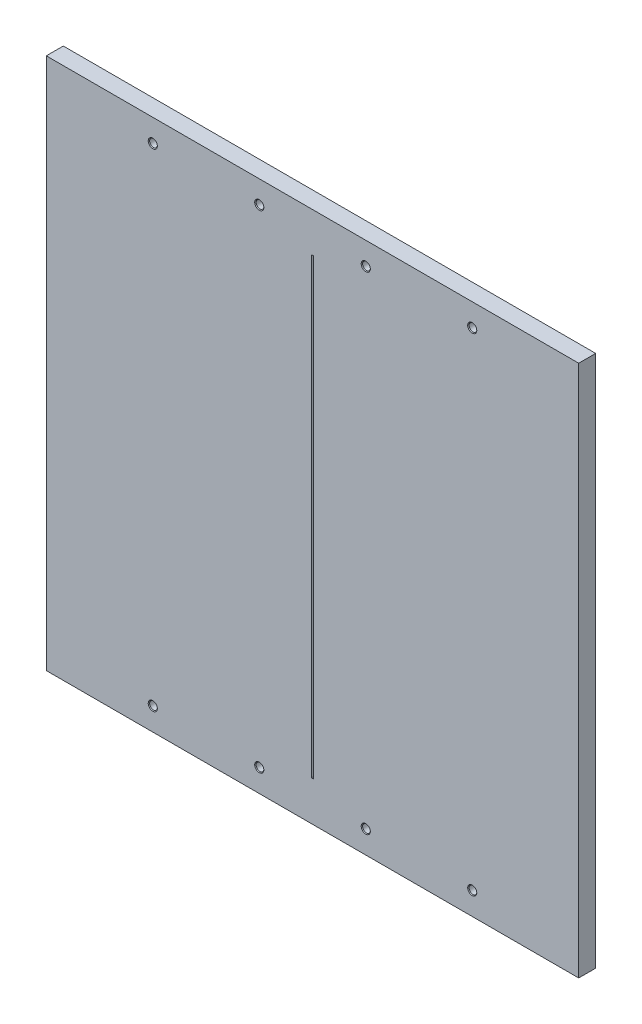
SolidWorks part; units mm, degrees
material "3.0205 (EN-AW 1200)"
ref_plane "Piano frontale" through (0, 0, 0) normal (0, 0, 1) x (1, 0, 0)
ref_plane "Piano superiore" through (0, 0, 0) normal (0, 1, 0) x (1, 0, 0)
ref_plane "Piano destro" through (0, 0, 0) normal (1, 0, 0) x (0, 0, -1)
sketch "Schizzo1" plane through (0, 0, 0) normal (0, 0, 1) x (1, 0, 0)
  line L1 (-235, -235) -> (235, -235)
  line L2 (-235, -235) -> (-235, 235)
  line L3 (-235, 235) -> (235, 235)
  line L4 (235, -235) -> (235, 235)
  line L5 (-235, -235) -> (235, 235) construction
  line L6 (-235, 235) -> (235, -235) construction
  point P0 (0, 0)
  dimension "D1" = 470
  dimension "D2" = 470
extrude "Estrusione-Estrusione1" add sketch "Schizzo1" along normal blind 15
hole_wizard "Foro filettato M8-1" positions "Schizzo8" profile "Schizzo10" tap size "M8" standard "ISO"
sketch "Schizzo8" plane through (0, 0, 15) normal (0, 0, 1) x (1, 0, 0)
  line L0 (-235, 215) -> (235, 215) construction
  line L1 (-235, 235) -> (-235, -235) construction
  line L2 (235, -235) -> (235, 235) construction
  line L4 (235, 235) -> (-235, 235) construction
  line L6 (-235, -215) -> (235, -215) construction
  line L8 (-235, -235) -> (235, -235) construction
  line L9 (-141, 215) -> (-141, -215) construction
  line L11 (-47, 215) -> (-47, -215) construction
  line L13 (47, 215) -> (47, -215) construction
  line L15 (141, 215) -> (141, -215) construction
  point P0 (-141, 215)
  point P2 (-47, 215)
  point P4 (47, 215)
  point P6 (141, 215)
  point P8 (-141, -215)
  point P10 (-47, -215)
  point P14 (141, -215)
  point P16 (47, -215)
  dimension "D1" = 20
  dimension "D2" = 20
  dimension "D3" = 94
  dimension "D4" = 94
  dimension "D5" = 94
  dimension "D6" = 94
sketch "Schizzo10" plane through (-141, 215, 15) normal (1, 0, 0) x (0, -1, 0)
  line L0 (0, 0) -> (0, 24.2929)
  line L1 (0, 24.2929) -> (3.4, 22.25)
  line L2 (3.4, 22.25) -> (3.4, 0.625)
  line L3 (3.4, 0.625) -> (4.025, 0)
  line L5 (4.025, 0) -> (0, 0)
  line L6 (-3.4, 0.625) -> (-4.025, 0) construction
  line L10 (0, 24.2929) -> (-3.4, 22.25) construction
  line L11 (0, -6.35) -> (0, 107.95) construction
  dimension "Tap Drill Dia." = 6.8
  dimension "Tap Drill Depth" = 22.25
  dimension "Near C'Sink Dia." = 8.05
  dimension "Near C'Sink Angle" = 90
  dimension "Drill Angle" = 118
cosmetic thread "Filettatura del foro1" parameters "D1"=16, "D2"=8
cosmetic thread "Filettatura del foro2" parameters "D1"=16, "D2"=8
cosmetic thread "Filettatura del foro3" parameters "D1"=16, "D2"=8
cosmetic thread "Filettatura del foro4" parameters "D1"=16, "D2"=8
cosmetic thread "Filettatura del foro5" parameters "D1"=16, "D2"=8
cosmetic thread "Filettatura del foro6" parameters "D1"=16, "D2"=8
cosmetic thread "Filettatura del foro7" parameters "D1"=16, "D2"=8
cosmetic thread "Filettatura del foro8" parameters "D1"=16, "D2"=8
sketch "Schizzo11" plane through (0, 0, 15) normal (0, 0, 1) x (1, 0, 0)
  line L1 (-1, 200) -> (1, 200)
  line L2 (-1, 200) -> (-1, -200)
  line L3 (-1, -200) -> (1, -200)
  line L4 (1, 200) -> (1, -200)
  line L5 (-1, 200) -> (1, -200) construction
  line L6 (-1, -200) -> (1, 200) construction
  point P0 (0, 0)
  dimension "D1" = 400
  dimension "D2" = 2
extrude "Taglio-Estrusione1" cut sketch "Schizzo11" against normal blind 5
